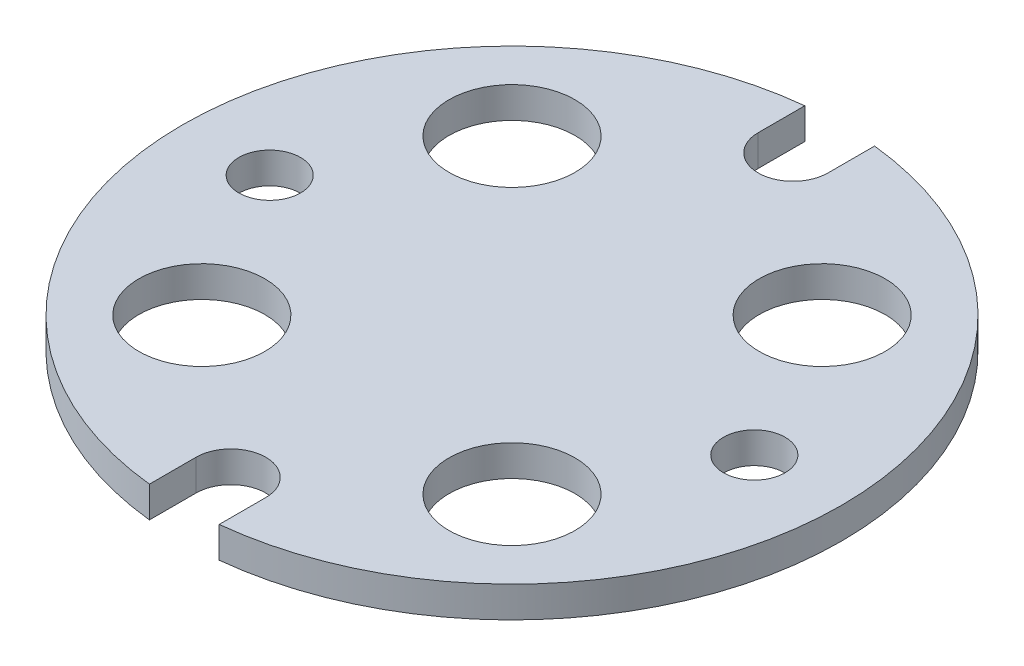
SolidWorks part; units mm, degrees
ref_plane "Front Plane" through (0, 0, 0) normal (0, 0, 1) x (1, 0, 0)
ref_plane "Top Plane" through (0, 0, 0) normal (0, 1, 0) x (1, 0, 0)
ref_plane "Right Plane" through (0, 0, 0) normal (1, 0, 0) x (0, 0, -1)
sketch "Sketch1" plane through (0, 0, 0) normal (0, 1, 0) x (1, 0, 0)
  circle A0 centre (0, 0) radius 17
  dimension "D1" = 34
extrude "Boss-Extrude1" add sketch "Sketch1" along normal blind 1.6
sketch "Sketch2" plane through (0, 0, 0) normal (0, -1, 0) x (1, 0, 0)
  line L0 (-1.8, 14.5) -> (-1.8, 16.9044)
  line L1 (1.8, 14.5) -> (1.8, 16.9044)
  line L2 (1.8, -14.5) -> (1.8, -16.9044)
  line L3 (-1.8, -14.5) -> (-1.8, -16.9044)
  circle A0 centre (12.5, 0) radius 1.59
  circle A1 centre (-12.5, 0) radius 1.59
  circle A2 centre (8, 8) radius 3.25
  circle A3 centre (8, -8) radius 3.25
  circle A4 centre (-8, -8) radius 3.25
  circle A5 centre (-8, 8) radius 3.25
  arc A6 (-1.8, 14.5) -> (1.8, 14.5) centre (0, 14.5) ccw
  circle A7 centre (0, 0) radius 17 construction
  arc A8 (1.8, -14.5) -> (-1.8, -14.5) centre (0, -14.5) ccw
  arc A9 (-1.8, 16.9044) -> (1.8, 16.9044) centre (0, 0) cw
  arc A10 (1.8, -16.9044) -> (-1.8, -16.9044) centre (0, 0) cw
  point P16 (0, 0)
  point P20 (0, 0)
  point P30 (0, 0)
  dimension "D2" = 3.18
  dimension "D4" = 3.18
  dimension "D5" = 6.5
  dimension "D7" = 8
  dimension "D9" = 14.5
  dimension "D10" = 3.6
  dimension "D1" = 12.5
  dimension "D3" = 12.5
  dimension "D6" = 8
  dimension "D8" = 4
  dimension "D11" = 2
extrude "Cut-Extrude1" cut sketch "Sketch2" against normal through all
